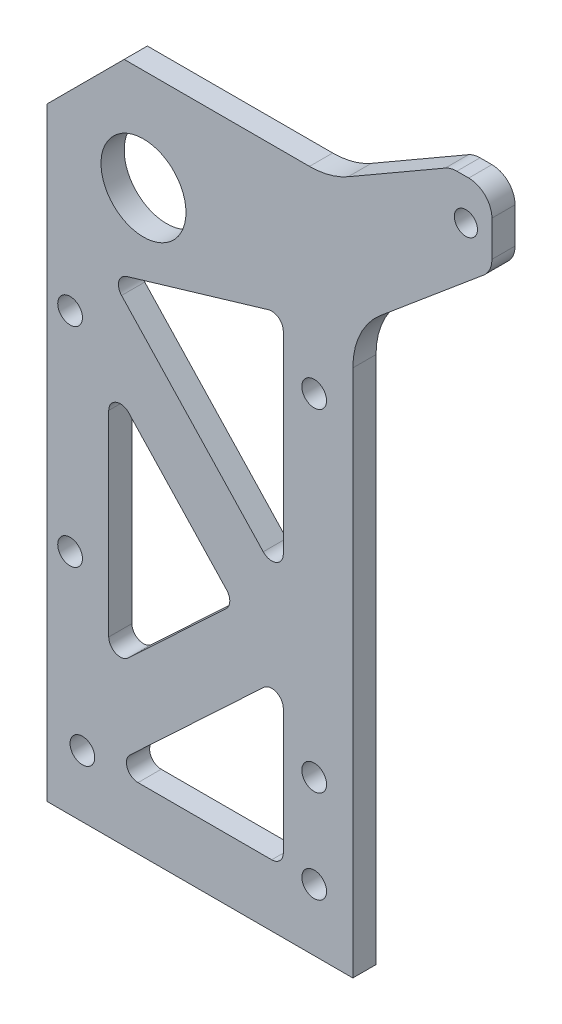
SolidWorks part; units mm, degrees
ref_plane "前视基准面" through (0, 0, 0) normal (0, 0, 1) x (1, 0, 0)
ref_plane "上视基准面" through (0, 0, 0) normal (0, 1, 0) x (1, 0, 0)
ref_plane "右视基准面" through (0, 0, 0) normal (1, 0, 0) x (0, 0, -1)
ref_plane "基准面1" through (0, 0, 4) normal (0, 0, 1) x (1, 0, 0)
sketch "草图1" plane through (0, 0, 4) normal (0, 0, 1) x (1, 0, 0)
  line L0 (27.5, -75) -> (27.5, -38.0701)
  line L1 (-12.0937, 15) -> (-12.0937, -75)
  line L2 (-12.0937, 15) -> (27.5, 15)
  line L3 (27.5, 15) -> (27.5, -38.0701)
  line L6 (-12.0937, -75) -> (27.5, -75)
  circle A0 centre (22.5, -12) radius 1.6
  circle A1 centre (22.5, -55) radius 1.6
  circle A2 centre (22.5, -67) radius 1.6
  circle A3 centre (-7.5, -67) radius 1.6
  circle A4 centre (-9.0937, -18.5) radius 1.6
  circle A5 centre (0.4063, 0) radius 6.075
  circle A6 centre (-9.0937, -45.5) radius 1.6
  dimension "D4" = 3.2
  dimension "D6" = 12.5
  dimension "D14" = 27
  dimension "D16" = 5
  dimension "D19" = 8
  dimension "D21" = 15
  dimension "D18" = 30
  dimension "D23" = 12.15
  dimension "D2" = 90
  dimension "D12" = 3
  dimension "D13" = 3
  dimension "D15" = 5
  dimension "D17" = 5
  dimension "D20" = 8
  dimension "D22" = 27
extrude "凸台-拉伸1" add sketch "草图1" against normal blind 3
sketch "草图6" plane through (0, 0, 4) normal (0, 0, 1) x (1, 0, 0)
  circle A0 centre (0.4063, 0) radius 5.5
  circle A1 centre (0.4063, 0) radius 6.075
  circle A2 centre (0.4063, 0) radius 6.075 construction
  dimension "D1" = 12.15
  dimension "D2" = 11
extrude "凸台-拉伸3" add sketch "草图6" against normal blind 3
sketch "草图7" plane through (0, 0, 4) normal (0, 0, 1) x (1, 0, 0)
  line L0 (16.5735, -5.5619) -> (-1.7638, -11)
  line L1 (-2.4317, -13.4639) -> (15.9056, -33.0259)
  line L2 (18.5, -32) -> (18.5, -7)
  line L3 (-4.0937, -27.182) -> (-4.0937, -52.5726)
  line L4 (-1.5679, -53.6669) -> (11.101, -41.7912)
  line L5 (11.1695, -39.671) -> (-1.4994, -26.1561)
  line L6 (15.9741, -48.1884) -> (-1.3261, -64.4056)
  line L7 (-0.3003, -67) -> (17, -67)
  line L8 (18.5, -65.5) -> (18.5, -49.2827)
  line L12 (-12.0937, -75) -> (27.5, -75) construction
  line L13 (-12.0937, 15) -> (-12.0937, -75) construction
  line L14 (27.5, -75) -> (27.5, 15) construction
  line L16 (27.5, 15) -> (-12.0937, 15) construction
  arc A5 (17, -67) -> (18.5, -65.5) centre (17, -65.5) ccw
  arc A6 (15.9741, -48.1884) -> (18.5, -49.2827) centre (17, -49.2827) cw
  arc A7 (-1.3261, -64.4056) -> (-0.3003, -67) centre (-0.3003, -65.5) ccw
  arc A8 (-4.0937, -52.5726) -> (-1.5679, -53.6669) centre (-2.5937, -52.5726) ccw
  arc A9 (-4.0937, -27.182) -> (-1.4994, -26.1561) centre (-2.5937, -27.182) cw
  arc A10 (11.101, -41.7912) -> (11.1695, -39.671) centre (10.0751, -40.6968) ccw
  arc A11 (15.9056, -33.0259) -> (18.5, -32) centre (17, -32) ccw
  arc A12 (16.5735, -5.5619) -> (18.5, -7) centre (17, -7) cw
  arc A13 (-1.7638, -11) -> (-2.4317, -13.4639) centre (-1.3373, -12.4381) ccw
  point P8 (0, -29.5324)
  point P10 (19.5, 0.8694)
  point P13 (15.4315, -40.9455)
  point P14 (-2.1492, -24.6806)
  point P15 (19.5, -38.2608)
  point P16 (19.5, -6.894)
  point P21 (19.5, -30.9552)
  point P22 (19.5, -26.3237)
  point P23 (19.5, -38.1586)
  point P24 (14.8072, -40.2591)
  point P25 (0, 0)
  point P26 (16.7692, -0.4879)
  point P27 (2.8247, -6.798)
  point P28 (16.7692, -3.7599)
  point P29 (0, 0)
  point P30 (15.4279, -50.017)
  point P31 (14.7958, -48.8077)
  point P38 (-4.0937, -67)
  point P47 (18.5, -35.7935)
  point P52 (-4.0937, -11.6909)
  point P53 (15.0276, -29.8019)
  point P54 (-1.2628, -6.7012)
  point P55 (-4.0937, -28.7937)
  point P56 (0, 0)
  point P57 (18.5, -7.3849)
  dimension "D8" = 1.5
  dimension "D1" = 8
  dimension "D2" = 8
  dimension "D3" = 8
  dimension "D4" = 9
  dimension "D5" = 25
  dimension "D6" = 8
  dimension "D7" = 22
  dimension "D9" = 26
extrude "切除-拉伸3" cut sketch "草图7" against normal blind 10
sketch "草图8" plane through (0, 0, 4) normal (0, 0, 1) x (1, 0, 0)
  line L1 (-12.0937, 15) -> (15.0982, 15)
  line L2 (-12.0937, 15) -> (-12.0937, 35)
  line L3 (-12.0937, 35) -> (15.0982, 35)
  line L5 (27.5, 15) -> (15.0982, 15)
  line L6 (27.5, 15) -> (27.5, 35)
  line L7 (27.5, 35) -> (15.0982, 35)
  dimension "D1" = 20
extrude "凸台-拉伸4" add sketch "草图8" against normal up to surface (3 mm away) up to face at (1.7911, -40.1669, 1)
sketch "草图9" plane through (0, 0, 4) normal (0, 0, 1) x (1, 0, 0)
  line L1 (27.5, 35) -> (-12.0937, 35) construction
  line L3 (27.5, 13.166) -> (27.5, 35)
  line L4 (27.5, 35) -> (9.9503, 35)
  line L6 (-3.0878, 35) -> (-12.0937, 35)
  line L12 (-3.0878, 35) -> (9.9503, 35)
  line L15 (-12.0937, 24.51) -> (-12.0937, 35)
  line L16 (27.5, 13.166) -> (-12.0937, 13.166)
  line L19 (-12.0937, 35) -> (-12.0937, -75) construction
  line L20 (-12.0937, 13.166) -> (-12.0937, 24.51)
extrude "切除-拉伸4" cut sketch "草图9" against normal blind 10
sketch "草图10" plane through (0, 0, 4) normal (0, 0, 1) x (1, 0, 0)
  line L1 (27.5, -75) -> (27.5, 13.166) construction
  line L5 (27.5, 13.166) -> (27.5, 2.9978)
  line L7 (-12.0937, 13.166) -> (27.5, 13.166) construction
  line L8 (24.571, 13.166) -> (27.5, 13.166)
  line L23 (47.5, 14.8254) -> (27.5, -1.9566)
  line L24 (27.5, -1.9566) -> (27.5, 2.9978)
  line L26 (40.1594, 22.166) -> (47.5, 22.166)
  line L29 (24.571, 13.166) -> (40.1594, 22.166)
  line L30 (47.5, 14.8254) -> (47.5, 22.166)
  dimension "D1" = 20
  dimension "D2" = 130
  dimension "D3" = 9
  dimension "D4" = 150
extrude "凸台-拉伸5" add sketch "草图10" against normal blind 3
sketch "草图11" plane through (0, 0, 4) normal (0, 0, 1) x (1, 0, 0)
  circle A0 centre (42.1346, 16.9385) radius 1.5
extrude "切除-拉伸5" cut sketch "草图11" against normal blind 10
sketch "Sketch1" plane through (47.5, 0, 0) normal (1, 0, 0) x (0, 0, -1)
  line L1 (-8.224, 24.7497) -> (4.7932, 24.7497)
  line L2 (-8.224, 24.7497) -> (-8.224, 10.8332)
  line L3 (-8.224, 10.8332) -> (4.7932, 10.8332)
  line L4 (4.7932, 24.7497) -> (4.7932, 10.8332)
extrude "Cut-Extrude1" cut sketch "Sketch1" against normal blind 2
chamfer "Chamfer1" distance 10 angle 45 1 edges at (-12.0937, 13.166, 2.5)
fillet "Fillet1" radius 10 2 edges at (24.571, 13.166, 2.5) (27.5, -1.9566, 2.5)
fillet "Fillet2" radius 3 3 edges at (45.5, 13.1472, 2.5) (40.1594, 22.166, 2.5) (45.5, 22.166, 2.5)
